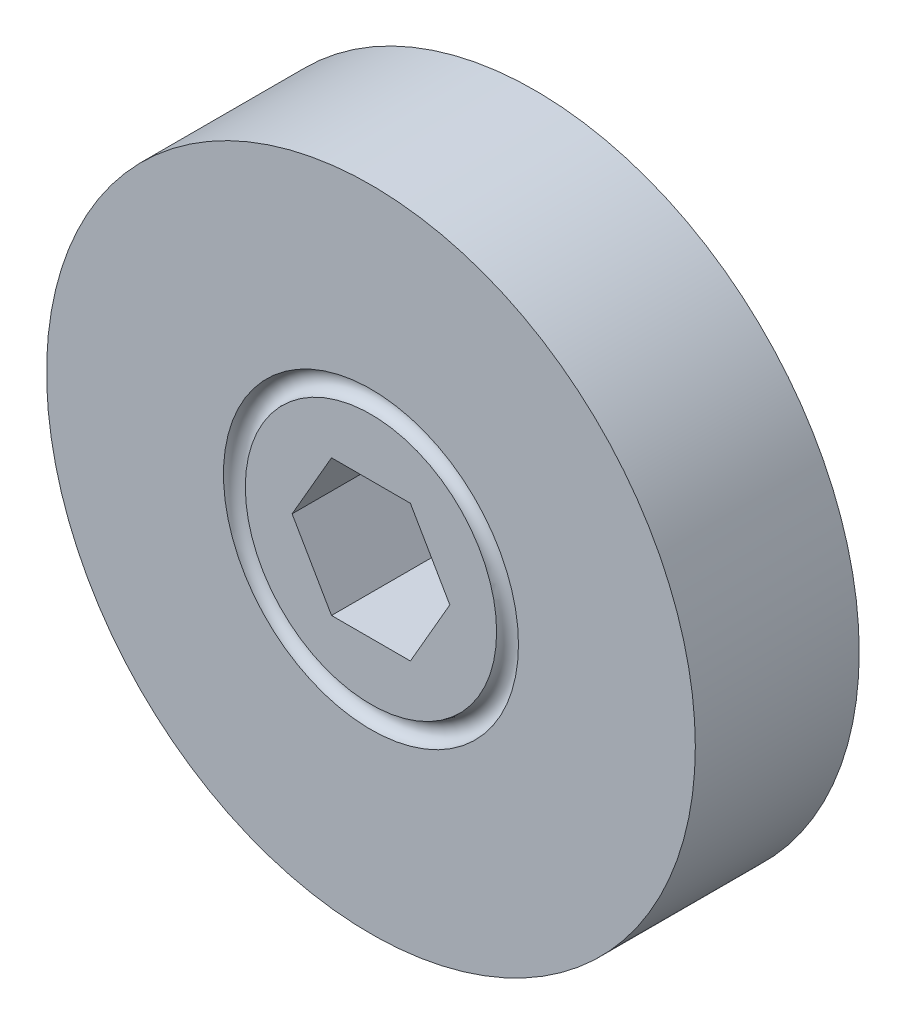
SolidWorks part; units mm, degrees
ref_plane "Front Plane" through (0, 0, 0) normal (0, 0, 1) x (1, 0, 0)
ref_plane "Top Plane" through (0, 0, 0) normal (0, 1, 0) x (1, 0, 0)
ref_plane "Right Plane" through (0, 0, 0) normal (1, 0, 0) x (0, 0, -1)
sketch "Sketch1" plane through (0, 0, 0) normal (1, 0, 0) x (0, 0, -1)
  line L0 (0, 0) -> (0, 30.1625) construction
  line L1 (-7.62, 30.1625) -> (7.62, 30.1625)
  line L2 (7.62, 30.1625) -> (7.62, 13.716)
  line L3 (7.62, 11.684) -> (7.62, 0)
  line L4 (-7.62, 11.684) -> (-7.62, 0)
  line L5 (-7.62, 30.1625) -> (-7.62, 13.716)
  line L6 (-7.62, 0) -> (7.62, 0)
  arc A0 (7.62, 13.716) -> (7.62, 11.684) centre (7.62, 12.7) ccw
  arc A1 (-7.62, 13.716) -> (-7.62, 11.684) centre (-7.62, 12.7) cw
  point P6 (0, 30.1625)
  dimension "D1" = 15.24
  dimension "D4" = 1.016
  dimension "D2" = 30.1625
  dimension "D3" = 12.7
revolve "Revolve1" add sketch "Sketch1" angle 360 about L6
sketch "Sketch2" plane through (0, 0, 7.62) normal (0, 0, 1) x (1, 0, 0)
  line L1 (-3.6662, 6.35) -> (-7.3323, 0)
  line L2 (-7.3323, 0) -> (-3.6662, -6.35)
  line L3 (-3.6662, -6.35) -> (3.6662, -6.35)
  line L4 (3.6662, -6.35) -> (7.3323, 0)
  line L5 (7.3323, 0) -> (3.6662, 6.35)
  line L6 (3.6662, 6.35) -> (-3.6662, 6.35)
  circle A0 centre (0, 0) radius 6.35 construction
  dimension "D1" = 12.7
extrude "Cut-Extrude1" cut sketch "Sketch2" against normal up to next
